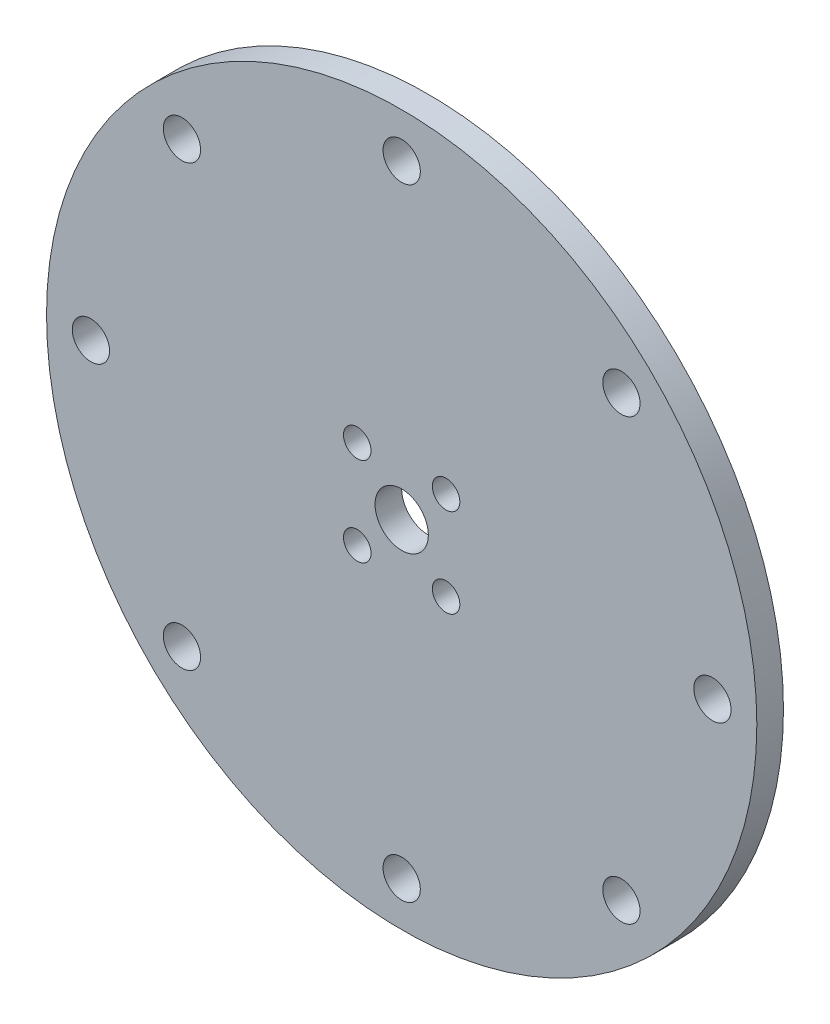
SolidWorks part; units mm, degrees
ref_plane "前视基准面" through (0, 0, 0) normal (0, 0, 1) x (1, 0, 0)
ref_plane "上视基准面" through (0, 0, 0) normal (0, 1, 0) x (1, 0, 0)
ref_plane "右视基准面" through (0, 0, 0) normal (1, 0, 0) x (0, 0, -1)
other "Configuration Table"
sketch "草图3" plane through (0, 0, 0) normal (0, 0, 1) x (1, 0, 0)
  circle A0 centre (0, 0) radius 48
  dimension "D1" = 96
extrude "凸台-拉伸2" add sketch "草图3" along normal blind 3
sketch "草图4" plane through (0, 0, 3) normal (0, 0, 1) x (1, 0, 0)
  circle A0 centre (0, 0) radius 3
  dimension "D1" = 6
extrude "切除-拉伸1" cut sketch "草图4" against normal blind 3
sketch "草图5" plane through (0, 0, 3) normal (0, 0, 1) x (1, 0, 0)
  line L0 (0, 0) -> (38, 0)
  line L1 (38, 0) -> (38, 10.5)
  line L2 (38, 0) -> (38, -10.5)
  line L3 (37.5, -11) -> (0.5, -11)
  line L4 (37.5, 11) -> (0.5, 11)
  line L5 (0, 11.5) -> (0, 12.5)
  line L6 (0.5, 13) -> (39.5, 13)
  line L7 (40, 12.5) -> (40, -12.5)
  line L8 (0, -11.5) -> (0, -12.5)
  line L9 (0.5, -13) -> (39.5, -13)
  arc A0 (0.5, -13) -> (0, -12.5) centre (0.5, -12.5) cw
  arc A1 (0, -11.5) -> (0.5, -11) centre (0.5, -11.5) cw
  arc A2 (39.5, -13) -> (40, -12.5) centre (39.5, -12.5) ccw
  arc A3 (37.5, -11) -> (38, -10.5) centre (37.5, -10.5) ccw
  arc A4 (40, 12.5) -> (39.5, 13) centre (39.5, 12.5) ccw
  arc A5 (38, 10.5) -> (37.5, 11) centre (37.5, 10.5) ccw
  arc A6 (0, 11.5) -> (0.5, 11) centre (0.5, 11.5) ccw
  arc A7 (0, 12.5) -> (0.5, 13) centre (0.5, 12.5) cw
  point P17 (40, -13)
  point P20 (38, -11)
  point P23 (40, 13)
  point P26 (38, 11)
  point P29 (0, 11)
  point P32 (0, 13)
  dimension "D7" = 0.5
  dimension "D1" = 38
  dimension "D2" = 11
  dimension "D3" = 11
  dimension "D4" = 2
  dimension "D5" = 40
  dimension "D6" = 26
extrude "凸台-拉伸3" add sketch "草图5" along normal blind 35 contours A7 L5 A6 L4 A5 L1 L2 A3 L3 A1 L8 A0 L9 A2 L7 A4 L6
sketch "草图6" plane through (40, 0, 0) normal (1, 0, 0) x (0, 0, -1)
  line L0 (-3, 0) -> (-25, 0)
  line L1 (-3, 48) -> (-3, -48) construction
  line L3 (-30, -5) -> (-20, -5)
  line L4 (-30, -5) -> (-30, 5)
  line L5 (-30, 5) -> (-20, 5)
  line L6 (-20, -5) -> (-20, 5)
  line L7 (-30, -5) -> (-20, 5) construction
  line L8 (-30, 5) -> (-20, -5) construction
  circle A0 centre (-25, 0) radius 3
  circle A1 centre (-30, 5) radius 1.5
  circle A2 centre (-20, 5) radius 1.5
  circle A3 centre (-20, -5) radius 1.5
  circle A4 centre (-30, -5) radius 1.5
  dimension "D2" = 6
  dimension "D5" = 3
  dimension "D1" = 22
  dimension "D3" = 10
  dimension "D4" = 10
  dimension "D6" = 4
extrude "切除-拉伸2" cut sketch "草图6" against normal blind 35
sketch "草图7" plane through (0, 0, 3) normal (0, 0, 1) x (1, 0, 0)
  line L0 (0, 0) -> (-35, 0)
  circle A4 centre (-35, 0) radius 1.55
  circle A5 centre (-24.7487, 24.7487) radius 1.55
  circle A6 centre (0, 35) radius 1.55
  circle A7 centre (24.7487, 24.7487) radius 1.55
  circle A8 centre (35, 0) radius 1.55
  circle A9 centre (24.7487, -24.7487) radius 1.55
  circle A10 centre (0, -35) radius 1.55
  circle A11 centre (-24.7487, -24.7487) radius 1.55
  dimension "D3" = 8
  dimension "D2" = 3.1
  dimension "D1" = 35
extrude "切除-拉伸5" cut sketch "草图7" against normal blind 35 contours A5 | A4 | A11 | A10 | A9 | A8 | A7 | A6
sketch "草图9" plane through (0, 0, 3) normal (0, 0, 1) x (1, 0, 0)
  circle A0 centre (0, 0) radius 40
  circle A1 centre (0, 0) radius 48
  dimension "D1" = 80
extrude "切除-拉伸6" cut sketch "草图9" against normal blind 35
sketch "草图10" plane through (0, 0, 3) normal (0, 0, 1) x (1, 0, 0)
  circle A0 centre (0, 0) radius 40
extrude "切除-拉伸7" cut sketch "草图10" along normal blind 35
sketch "草图11" plane through (40, 0, 0) normal (1, 0, 0) x (0, 0, -1)
  line L0 (-3, 40) -> (-3, -40) construction
  line L1 (-114.5882, 65.4325) -> (-3, 65.4325)
  line L2 (-114.5882, 65.4325) -> (-114.5882, -16.7911)
  line L3 (-114.5882, -16.7911) -> (-3, -16.7911)
  line L4 (-3, 65.4325) -> (-3, -16.7911)
  line L5 (-114.5882, 65.4325) -> (-3, -16.7911) construction
  line L6 (-114.5882, -16.7911) -> (-3, 65.4325) construction
  point P0 (-58.7941, 24.3207)
extrude "切除-拉伸8" cut sketch "草图11" against normal blind 35
sketch "草图12" plane through (0, 0, 3) normal (0, 0, 1) x (1, 0, 0)
  line L1 (-5, -5) -> (5, -5)
  line L2 (-5, -5) -> (-5, 5)
  line L3 (-5, 5) -> (5, 5)
  line L4 (5, -5) -> (5, 5)
  line L5 (-5, -5) -> (5, 5) construction
  line L6 (-5, 5) -> (5, -5) construction
  circle A0 centre (-5, 5) radius 1
  circle A1 centre (5, 5) radius 1
  circle A2 centre (5, -5) radius 1
  circle A3 centre (-5, -5) radius 1
  point P0 (0, 0)
  dimension "D3" = 2
  dimension "D1" = 10
  dimension "D2" = 10
extrude "切除-拉伸9" cut sketch "草图12" against normal blind 35 contours L3 A0 L2 | L2 A0 L3 | A3 | A2 | A1
sketch "草图13" plane through (0, 0, 3) normal (0, 0, 1) x (1, 0, 0)
  circle A0 centre (0, 35) radius 2.1
  circle A1 centre (24.7487, 24.7487) radius 2.1
  circle A2 centre (35, 0) radius 2.1
  circle A3 centre (24.7487, -24.7487) radius 2.1
  circle A4 centre (0, -35) radius 2.1
  circle A5 centre (-24.7487, -24.7487) radius 2.1
  circle A6 centre (-35, 0) radius 2.1
  circle A7 centre (-24.7487, 24.7487) radius 2.1
  dimension "D1" = 4.2
  dimension "D2" = 8
extrude "切除-拉伸10" cut sketch "草图13" against normal blind 35
sketch "草图14" plane through (0, 0, 3) normal (0, 0, 1) x (1, 0, 0)
  circle A0 centre (-5, 5) radius 1.55
  circle A1 centre (5, 5) radius 1.55
  circle A2 centre (5, -5) radius 1.55
  circle A3 centre (-5, -5) radius 1.55
  dimension "D1" = 3.1
  dimension "D2" = 4
extrude "切除-拉伸11" cut sketch "草图14" against normal blind 35
